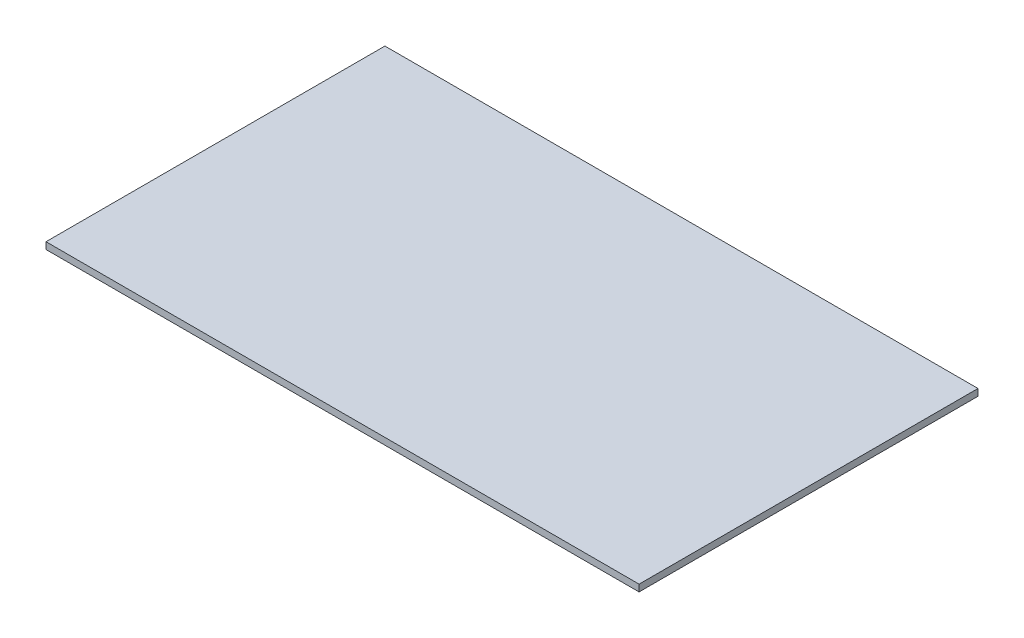
SolidWorks part; units mm, degrees
ref_plane "Front Plane" through (0, 0, 0) normal (0, 0, 1) x (1, 0, 0)
ref_plane "Top Plane" through (0, 0, 0) normal (0, 1, 0) x (1, 0, 0)
ref_plane "Right Plane" through (0, 0, 0) normal (1, 0, 0) x (0, 0, -1)
sketch "Sketch1" plane through (0, 0, 0) normal (0, 1, 0) x (1, 0, 0)
  line L0 (-35, 20) -> (35, -20) construction
  line L1 (-35, 20) -> (35, 20)
  line L2 (-35, 20) -> (-35, -20)
  line L3 (-35, -20) -> (35, -20)
  line L4 (35, 20) -> (35, -20)
  dimension "D1" = 70
  dimension "D2" = 40
extrude "Boss-Extrude1" add sketch "Sketch1" along normal blind 0.8
